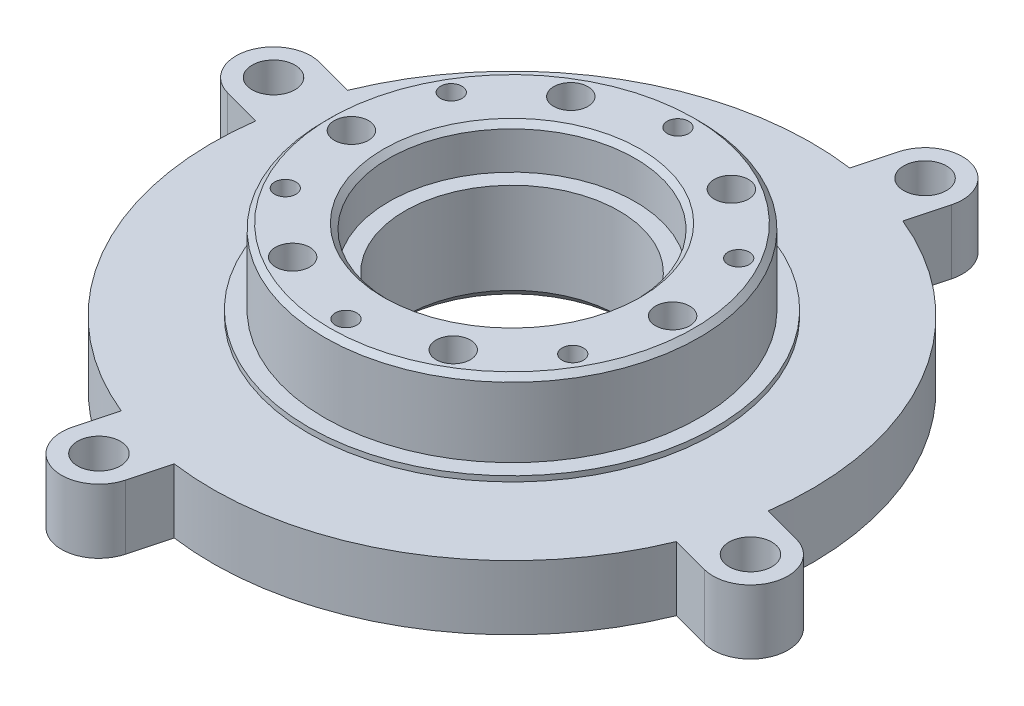
SolidWorks part; units mm, degrees
material "Like ABS"
ref_plane "Front Plane" through (0, 0, 0) normal (0, 0, 1) x (1, 0, 0)
ref_plane "Top Plane" through (0, 0, 0) normal (0, 1, 0) x (1, 0, 0)
ref_plane "Right Plane" through (0, 0, 0) normal (1, 0, 0) x (0, 0, -1)
sketch "Sketch1" plane through (0, 0, 0) normal (0, 1, 0) x (1, 0, 0)
  circle A0 centre (0, 0) radius 28
  dimension "D1" = 56
extrude "Boss-Extrude1" add sketch "Sketch1" along normal blind 6
sketch "Sketch2" plane through (0, 6, 0) normal (0, 1, 0) x (1, 0, 0)
  circle A0 centre (0, 0) radius 19
  dimension "D1" = 38
extrude "Boss-Extrude2" add sketch "Sketch2" along normal blind 0.5
sketch "Sketch3" plane through (0, 6.5, 0) normal (0, 1, 0) x (1, 0, 0)
  circle A0 centre (0, 0) radius 17.5
  dimension "D1" = 35
extrude "Boss-Extrude3" add sketch "Sketch3" along normal blind 7
sketch "Sketch4" plane through (0, 13.5, 0) normal (0, 1, 0) x (1, 0, 0)
  line L0 (0, 15.5) -> (0, 0) construction
  line L1 (0, 0) -> (7.75, 13.4234) construction
  circle A0 centre (0, 15.5) radius 1
  dimension "D3" = 2
  dimension "D1" = 30
  dimension "D2" = 15.5
extrude "Cut-Extrude1" cut sketch "Sketch4" against normal blind 3
pattern_circular "CirPattern1" count 6 over 360 about axis through (0, 0, 0) along (0, 1, 0) of "Cut-Extrude1"
sketch "Sketch5" plane through (0, 13.5, 0) normal (0, 1, 0) x (1, 0, 0)
  circle A0 centre (0, 0) radius 11.5
  dimension "D1" = 23
extrude "Cut-Extrude2" cut sketch "Sketch5" against normal blind 4
sketch "Sketch6" plane through (0, 9.5, 0) normal (0, 1, 0) x (1, 0, 0)
  circle A0 centre (0, 0) radius 10
  dimension "D1" = 20
extrude "Cut-Extrude3" cut sketch "Sketch6" against normal up to surface (9.5 mm away) up to face at (0, 0, 28)
sketch "Sketch7" plane through (0, 13.5, 0) normal (0, 1, 0) x (1, 0, 0)
  line L0 (0, 15.5) -> (0, 0) construction
  line L1 (0, 0) -> (7.5, 12.9904) construction
  circle A0 centre (7.5, 12.9904) radius 1.6
  dimension "D2" = 3.2
  dimension "D1" = 30
  dimension "D3" = 15
extrude "Cut-Extrude4" cut sketch "Sketch7" against normal up to surface (13.5 mm away) up to face at (0, 0, 10)
sketch "Sketch9" plane through (0, 0, 0) normal (0, -1, 0) x (1, 0, 0)
  circle A0 centre (7.5, -12.9904) radius 3.5
  dimension "D1" = 7
extrude "Cut-Extrude10" cut sketch "Sketch9" against normal blind 5
sketch "Sketch10" plane through (0, 0, 0) normal (0, -1, 0) x (1, 0, 0)
  circle A0 centre (7.5, -12.9904) radius 2
  dimension "D1" = 4
extrude "Cut-Extrude11" cut sketch "Sketch10" against normal blind 11
pattern_circular "CirPattern2" count 6 over 360 about axis through (0, 0, 0) along (0, 1, 0) of "Cut-Extrude4", "Cut-Extrude11", "Cut-Extrude10"
chamfer "Chamfer1" distance 1 angle 45 1 edges at (0, 0, 10)
chamfer "Chamfer2" distance 0.5 angle 45 2 edges at (0, 13.5, 11.5) (0, 13.5, 17.5)
sketch "Sketch13" plane through (0, 6, 0) normal (0, 1, 0) x (1, 0, 0)
  line L0 (0, 25) -> (0, 0) construction
  line L1 (0, 0) -> (7.2469, 27.0459) construction
  line L2 (7.2469, 27.0459) -> (9.0587, 33.8074) construction
  line L6 (0, 0) -> (-27.0459, 7.2469) construction
  line L7 (-27.0459, 7.2469) -> (-33.8074, 9.0587) construction
  line L8 (0, 0) -> (-26.3114, 9.5766) construction
  line L9 (3.0505, 34.8668) -> (2.4404, 27.8935) construction
  line L10 (2.4404, 27.8935) -> (0, 0) construction
  line L11 (0, 0) -> (4.8621, 27.5746) construction
  line L12 (4.8621, 27.5746) -> (6.0777, 34.4683) construction
  line L19 (-26.3114, 9.5766) -> (-32.8892, 11.9707) construction
  line L20 (0, 0) -> (-25.3766, 11.8333) construction
  line L21 (-25.3766, 11.8333) -> (-31.7208, 14.7916) construction
  line L27 (4.7721, 31.3325) -> (3.0277, 24.8224)
  line L28 (3.0277, 24.8224) -> (9.7891, 23.0106)
  line L29 (9.7891, 23.0106) -> (11.5335, 29.5208)
  circle A0 centre (8.1528, 30.4267) radius 1.6
  circle A4 centre (0, 0) radius 28 construction
  arc A7 (11.5335, 29.5208) -> (4.7721, 31.3325) centre (8.1528, 30.4267) ccw
  dimension "D4" = 3.2
  dimension "D5" = 90
  dimension "D6" = 10
  dimension "D1" = 15
  dimension "D2" = 28
  dimension "D3" = 7
  dimension "D7" = 5
  dimension "D10" = 5
  dimension "D11" = 5
extrude "Boss-Extrude4" add sketch "Sketch13" against normal up to surface (6 mm away) up to face at (0, 0, 11)
sketch "Sketch14" plane through (0, 6, 0) normal (0, 1, 0) x (1, 0, 0)
  circle A0 centre (8.1528, 30.4267) radius 2
  dimension "D1" = 4
extrude "Cut-Extrude12" cut sketch "Sketch14" against normal blind 4
pattern_circular "CirPattern3" count 4 over 360 about axis through (0, 0, 0) along (0, 1, 0) of "Cut-Extrude12", "Boss-Extrude4"
